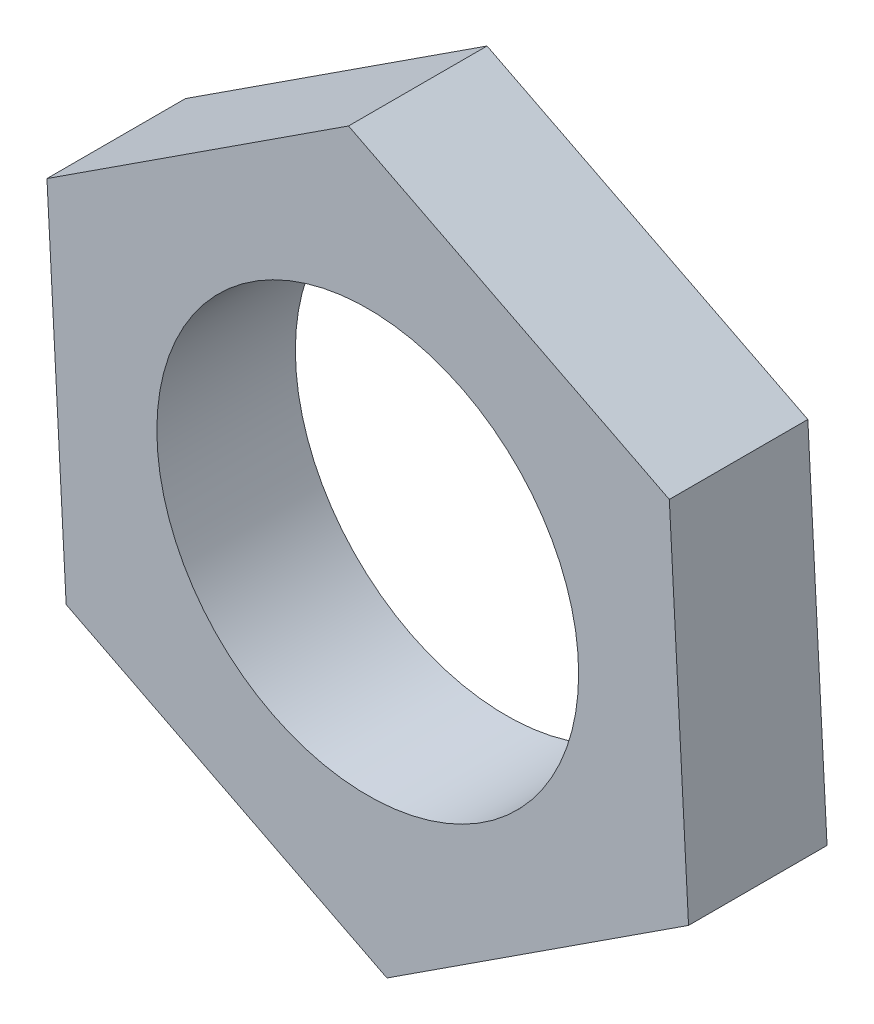
SolidWorks part; units mm, degrees
ref_plane "前视基准面" through (0, 0, 0) normal (0, 0, 1) x (1, 0, 0)
ref_plane "上视基准面" through (0, 0, 0) normal (0, 1, 0) x (1, 0, 0)
ref_plane "右视基准面" through (0, 0, 0) normal (1, 0, 0) x (0, 0, -1)
sketch "草图1" plane through (0, 0, 0) normal (0, 0, 1) x (1, 0, 0)
  line L1 (0.3053, -5.7076) -> (5.0956, -2.5894)
  line L2 (5.0956, -2.5894) -> (4.7903, 3.1182)
  line L3 (4.7903, 3.1182) -> (-0.3053, 5.7076)
  line L4 (-0.3053, 5.7076) -> (-5.0956, 2.5894)
  line L5 (-5.0956, 2.5894) -> (-4.7903, -3.1182)
  line L6 (-4.7903, -3.1182) -> (0.3053, -5.7076)
  circle A0 centre (0, 0) radius 4.95 construction
  circle A1 centre (0, 0) radius 3.35
  dimension "D2" = 6.7
  dimension "D1" = 9.9
extrude "凸台-拉伸2" add sketch "草图1" along normal blind 2.2
cosmetic thread "装饰螺纹线1" parameters "D2"=8
